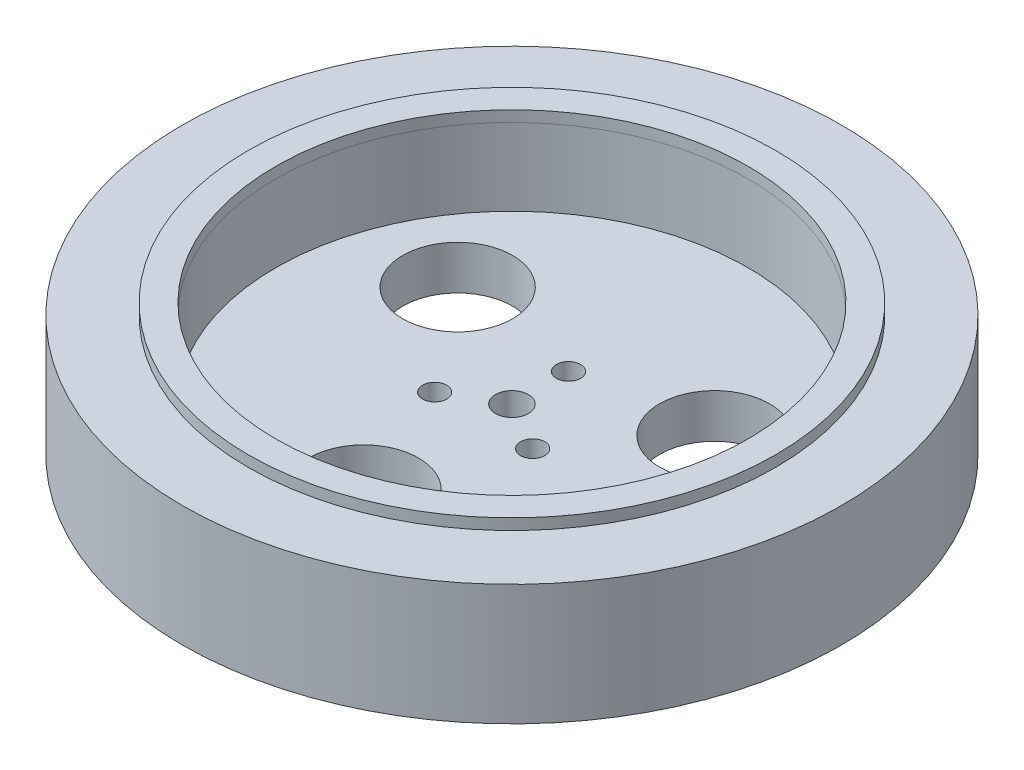
SolidWorks part; units mm, degrees
ref_plane "前视基准面" through (0, 0, 0) normal (0, 0, 1) x (1, 0, 0)
ref_plane "上视基准面" through (0, 0, 0) normal (0, 1, 0) x (1, 0, 0)
ref_plane "右视基准面" through (0, 0, 0) normal (1, 0, 0) x (0, 0, -1)
sketch "草图1" plane through (0, 0, 0) normal (0, 1, 0) x (1, 0, 0)
  circle A0 centre (0, 0) radius 24
  dimension "D1" = 48
extrude "凸台-拉伸1" add sketch "草图1" along normal blind 12
sketch "草图2" plane through (0, 12, 0) normal (0, 1, 0) x (1, 0, 0)
  circle A0 centre (0, 0) radius 21.5
  dimension "D1" = 43
extrude "切除-拉伸3" cut sketch "草图2" against normal blind 7 contours A0
sketch "草图3" plane through (0, 5, 0) normal (0, 1, 0) x (1, 0, 0)
  line L0 (-28.198, 0) -> (35.8349, 0) construction
  line L1 (0, 25.9787) -> (0, -25.5871) construction
  circle A0 centre (0, 0) radius 5.15 construction
  circle A1 centre (0, 5.15) radius 1.1
  circle A2 centre (4.46, -2.575) radius 1.1
  circle A3 centre (-4.46, -2.575) radius 1.1
  circle A4 centre (0, 0) radius 1.5
  point P15 (0, 0)
  dimension "D1" = 10.3
  dimension "D2" = 2.2
  dimension "D4" = 3
  dimension "D3" = 3
extrude "切除-拉伸4" cut sketch "草图3" against normal through all
sketch "草图5" plane through (0, 12, 0) normal (0, 1, 0) x (1, 0, 0)
  circle A0 centre (0, 0) radius 24
  circle A1 centre (0, 0) radius 30
  dimension "D1" = 60
  dimension "D2" = 48
extrude "凸台-拉伸2" add sketch "草图5" against normal blind 11 separate body
sketch "草图7" plane through (0, 0, 0) normal (0, -1, 0) x (1, 0, 0)
  circle A0 centre (0, 0) radius 24
extrude "切除-拉伸6" cut sketch "草图7" against normal blind 1
sketch "草图8" plane through (0, 12, 0) normal (0, 1, 0) x (1, 0, 0)
  circle A0 centre (0, 0) radius 21.5
  circle A1 centre (0, 0) radius 24
  circle A2 centre (0, 0) radius 24
  dimension "D1" = 0
extrude "凸台-拉伸4" add sketch "草图8" along normal blind 1 separate body
sketch "草图4" plane through (0, 5, 0) normal (0, 1, 0) x (1, 0, 0)
  line L0 (-30.9394, 0) -> (39.7513, 0) construction
  line L1 (0, 26.1092) -> (0, -26.1745) construction
  line L2 (0, 0) -> (-24.7927, 14.3141) construction
  circle A0 centre (0, 0) radius 13.5 construction
  circle A5 centre (-11.6913, 6.75) radius 5
  circle A10 centre (11.6913, 6.75) radius 5
  circle A15 centre (0, -13.5) radius 5
  point P16 (0, 0)
  point P31 (0, 0)
  dimension "D2" = 27
  dimension "D4" = 3
  dimension "D3" = 10
  dimension "D1" = 60
extrude "切除-拉伸8" cut sketch "草图4" against normal through all
